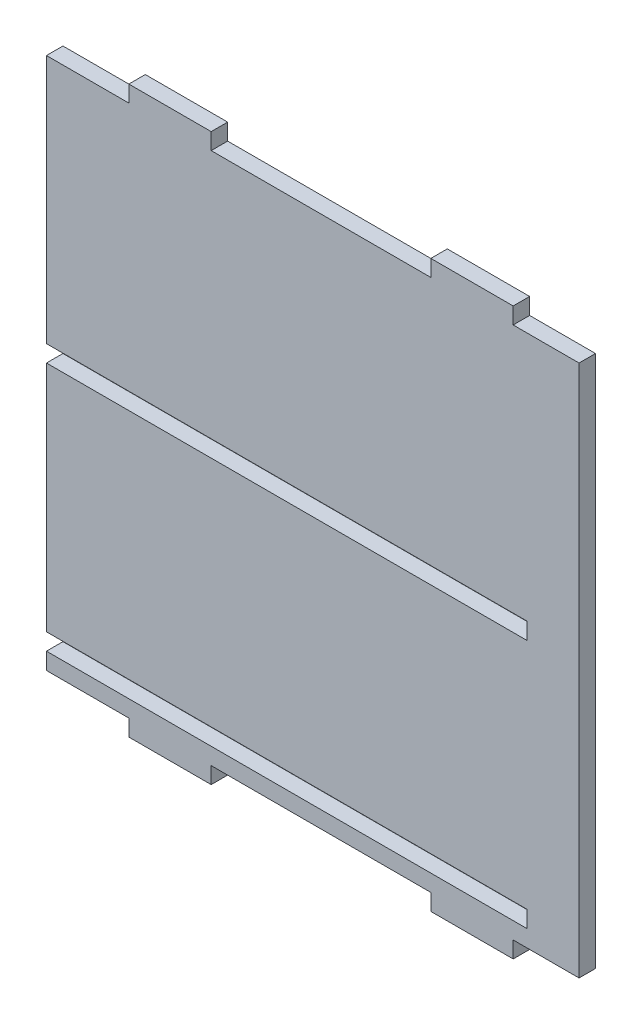
SolidWorks part; units mm, degrees
ref_plane "Plano frontal" through (0, 0, 0) normal (0, 0, 1) x (1, 0, 0)
ref_plane "Plano superior" through (0, 0, 0) normal (0, 1, 0) x (1, 0, 0)
ref_plane "Plano direito" through (0, 0, 0) normal (1, 0, 0) x (0, 0, -1)
sketch "Esboço1" plane through (0, 0, 0) normal (0, 0, 1) x (1, 0, 0)
  line L0 (-67, -97) -> (-97, -97)
  line L2 (-97, 97) -> (-97, -97)
  line L4 (97, 97) -> (97, -97)
  line L5 (-97, 97) -> (97, -97) construction
  line L6 (-97, -97) -> (97, 97) construction
  line L8 (-67, -97) -> (-67, -103)
  line L9 (-67, -103) -> (-37, -103)
  line L10 (-37, -97) -> (-37, -103)
  line L12 (43, -97) -> (43, -103)
  line L13 (43, -103) -> (73, -103)
  line L14 (73, -97) -> (73, -103)
  line L15 (-37, -97) -> (43, -97)
  line L16 (73, -97) -> (97, -97)
  line L17 (-67, 97) -> (-97, 97)
  line L19 (-67, 97) -> (-67, 103)
  line L20 (-67, 103) -> (-37, 103)
  line L21 (-37, 97) -> (-37, 103)
  line L23 (43, 97) -> (43, 103)
  line L24 (43, 103) -> (73, 103)
  line L25 (73, 97) -> (73, 103)
  line L26 (43, 97) -> (-37, 97)
  line L27 (73, 97) -> (97, 97)
  point P0 (0, 0)
  dimension "D1" = 194
  dimension "D2" = 194
  dimension "D3" = 30
  dimension "D4" = 30
  dimension "D5" = 6
  dimension "D6" = 6
  dimension "D7" = 30
  dimension "D8" = 24
  dimension "D9" = 6
  dimension "D10" = 6
  dimension "D11" = 6
  dimension "D12" = 6
  dimension "D13" = 30
  dimension "D14" = 30
  dimension "D15" = 30
  dimension "D16" = 24
  dimension "D17" = 6
  dimension "D18" = 6
extrude "Ressalto-extrusão1" add sketch "Esboço1" along normal blind 6
sketch "Esboço2" plane through (0, 0, 6) normal (0, 0, 1) x (1, 0, 0)
  line L0 (-97, 97) -> (-97, -97) construction
  line L1 (-97, 0) -> (78, 0)
  line L2 (-97, 0) -> (-97, 6.1)
  line L3 (-97, 6.1) -> (78, 6.1)
  line L4 (78, 0) -> (78, 6.1)
  line L6 (-97, -97) -> (-67, -97) construction
  line L7 (-97, -90.9) -> (78, -90.9)
  line L8 (-97, -90.9) -> (-97, -84.8)
  line L9 (-97, -84.8) -> (78, -84.8)
  line L10 (78, -90.9) -> (78, -84.8)
  dimension "D1" = 6.1
  dimension "D2" = 175
  dimension "D3" = 6.1
  dimension "D4" = 175
  dimension "D5" = 6.1
extrude "Corte-extrusão1" cut sketch "Esboço2" against normal blind 10
